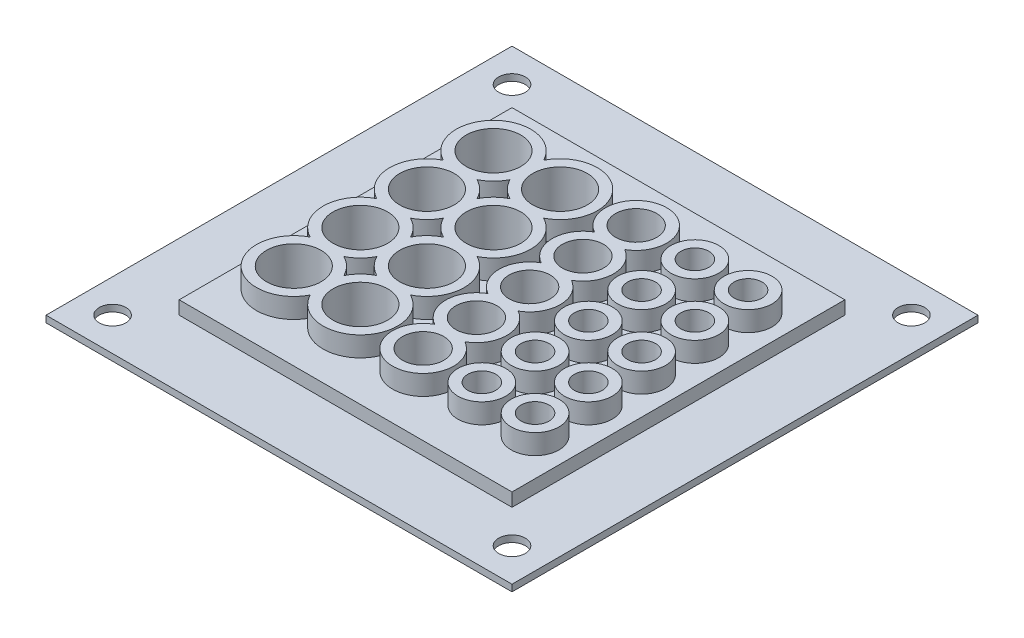
SolidWorks part; units mm, degrees
ref_plane "Front Plane" through (0, 0, 0) normal (0, 0, 1) x (1, 0, 0)
ref_plane "Top Plane" through (0, 0, 0) normal (0, 1, 0) x (1, 0, 0)
ref_plane "Right Plane" through (0, 0, 0) normal (1, 0, 0) x (0, 0, -1)
sketch "Sketch1" plane through (0, 0, 0) normal (0, 1, 0) x (1, 0, 0)
  line L0 (-25, 25) -> (25, 25) construction
  line L1 (25, 0) -> (-25, 0)
  line L2 (25, 0) -> (25, 50)
  line L3 (25, 50) -> (-25, 50)
  line L4 (-25, 0) -> (-25, 50)
  circle A0 centre (-17.7782, 10) radius 4.1
  circle A1 centre (-17.7782, 20) radius 4.1
  circle A2 centre (-17.7782, 30) radius 4.1
  circle A3 centre (-17.7782, 40) radius 4.1
  circle A4 centre (2.6548, 9) radius 3.1
  circle A5 centre (2.6548, 17) radius 3.1
  circle A6 centre (2.6548, 25) radius 3.1
  circle A7 centre (2.6548, 33) radius 3.1
  circle A8 centre (2.6548, 41) radius 3.1
  circle A9 centre (11.4667, 9) radius 2.1
  circle A10 centre (19.4667, 9) radius 2.1
  circle A11 centre (19.4667, 17) radius 2.1
  circle A12 centre (19.4667, 25) radius 2.1
  circle A13 centre (19.4667, 33) radius 2.1
  circle A14 centre (19.4667, 41) radius 2.1
  circle A15 centre (11.4667, 17) radius 2.1
  circle A16 centre (11.4667, 25) radius 2.1
  circle A17 centre (11.4667, 33) radius 2.1
  circle A18 centre (11.4667, 41) radius 2.1
  circle A19 centre (-7.7782, 10) radius 4.1
  circle A20 centre (-7.7782, 20) radius 4.1
  circle A21 centre (-7.7782, 30) radius 4.1
  circle A22 centre (-7.7782, 40) radius 4.1
  point P0 (0, 0)
  point P9 (0, 0)
  point P55 (0, 0)
  point P56 (2.6548, 25)
  point P57 (0, 0)
  point P58 (-7.7782, 20)
  dimension "D3" = 8.2
  dimension "D6" = 6.2
  dimension "D9" = 4.2
  dimension "D1" = 50
  dimension "D2" = 50
  dimension "D5" = 10
  dimension "D8" = 8
  dimension "D12" = 8
  dimension "D4" = 2
  dimension "D7" = 5
  dimension "D10" = 2
  dimension "D11" = 5
  dimension "D13" = 4
extrude "Boss-Extrude1" add sketch "Sketch1" along normal mid plane 3
sketch "Sketch2" plane through (0, 1.5, 0) normal (0, 1, 0) x (1, 0, 0)
  circle A1 centre (-17.7782, 10) radius 4.1
  circle A2 centre (-17.7782, 10) radius 4.1
  circle A3 centre (-17.7782, 20) radius 4.1
  circle A4 centre (-17.7782, 20) radius 4.1
  circle A5 centre (-17.7782, 30) radius 4.1
  circle A6 centre (-17.7782, 30) radius 4.1
  circle A7 centre (2.6548, 17) radius 3.1
  circle A8 centre (2.6548, 17) radius 3.1
  circle A9 centre (-17.7782, 40) radius 4.1
  circle A10 centre (-17.7782, 40) radius 4.1
  circle A11 centre (2.6548, 9) radius 3.1
  circle A12 centre (2.6548, 9) radius 3.1
  circle A13 centre (2.6548, 25) radius 3.1
  circle A14 centre (2.6548, 25) radius 3.1
  circle A15 centre (2.6548, 33) radius 3.1
  circle A16 centre (2.6548, 33) radius 3.1
  circle A17 centre (2.6548, 41) radius 3.1
  circle A18 centre (2.6548, 41) radius 3.1
  circle A19 centre (11.4667, 9) radius 2.1
  circle A20 centre (11.4667, 9) radius 2.1
  circle A21 centre (-7.7782, 10) radius 4.1
  circle A22 centre (-7.7782, 10) radius 4.1
  circle A23 centre (19.4667, 9) radius 2.1
  circle A24 centre (19.4667, 9) radius 2.1
  circle A25 centre (19.4667, 17) radius 2.1
  circle A26 centre (19.4667, 17) radius 2.1
  circle A27 centre (19.4667, 25) radius 2.1
  circle A28 centre (19.4667, 25) radius 2.1
  circle A29 centre (19.4667, 33) radius 2.1
  circle A30 centre (19.4667, 33) radius 2.1
  circle A31 centre (19.4667, 41) radius 2.1
  circle A32 centre (19.4667, 41) radius 2.1
  circle A33 centre (11.4667, 17) radius 2.1
  circle A34 centre (11.4667, 17) radius 2.1
  circle A35 centre (11.4667, 25) radius 2.1
  circle A36 centre (11.4667, 25) radius 2.1
  circle A37 centre (11.4667, 33) radius 2.1
  circle A38 centre (11.4667, 33) radius 2.1
  circle A39 centre (11.4667, 41) radius 2.1
  circle A40 centre (11.4667, 41) radius 2.1
  circle A41 centre (-7.7782, 20) radius 4.1
  circle A42 centre (-7.7782, 20) radius 4.1
  circle A43 centre (-7.7782, 30) radius 4.1
  circle A44 centre (-7.7782, 30) radius 4.1
  circle A45 centre (-7.7782, 40) radius 4.1
  circle A46 centre (-7.7782, 40) radius 4.1
  dimension "D1" = 0
  dimension "D2" = 0
  dimension "D3" = 0
  dimension "D4" = 0
  dimension "D5" = 0
  dimension "D6" = 0
  dimension "D7" = 0
  dimension "D8" = 0
  dimension "D9" = 0
  dimension "D10" = 0
  dimension "D11" = 0
  dimension "D12" = 0
  dimension "D13" = 0
  dimension "D14" = 0
  dimension "D15" = 0
  dimension "D16" = 0
  dimension "D17" = 0
  dimension "D18" = 0
  dimension "D19" = 0
  dimension "D20" = 0
  dimension "D21" = 0
  dimension "D22" = 0
  dimension "D23" = 0
extrude "Extrude-Thin1" add sketch "Sketch2" along normal blind 3 thin
sketch "Sketch3" plane through (0, -1.5, 0) normal (0, -1, 0) x (1, 0, 0)
  line L0 (-35, 10) -> (-35, -60)
  line L1 (-35, -60) -> (35, -60)
  line L2 (35, -60) -> (35, 10)
  line L3 (35, 10) -> (-35, 10)
  line L4 (-25, 0) -> (-25, -50)
  line L5 (-25, -50) -> (25, -50)
  line L6 (25, -50) -> (25, 0)
  line L7 (25, 0) -> (-25, 0)
  line L8 (-25, 0) -> (-25, -50)
  line L9 (-25, -50) -> (25, -50)
  line L10 (25, -50) -> (25, 0)
  line L11 (25, 0) -> (-25, 0)
  line L12 (30, 5) -> (-30, 5) construction
  line L13 (-30, 5) -> (-30, -55) construction
  line L14 (-30, -55) -> (30, -55) construction
  line L15 (30, -55) -> (30, 5) construction
  circle A0 centre (-30, 5) radius 2
  circle A1 centre (30, 5) radius 2
  circle A2 centre (30, -55) radius 2
  circle A3 centre (-30, -55) radius 2
  dimension "D4" = 4
  dimension "D1" = 0
  dimension "D2" = 10
  dimension "D3" = 5
extrude "Boss-Extrude2" add sketch "Sketch3" against normal blind 1
